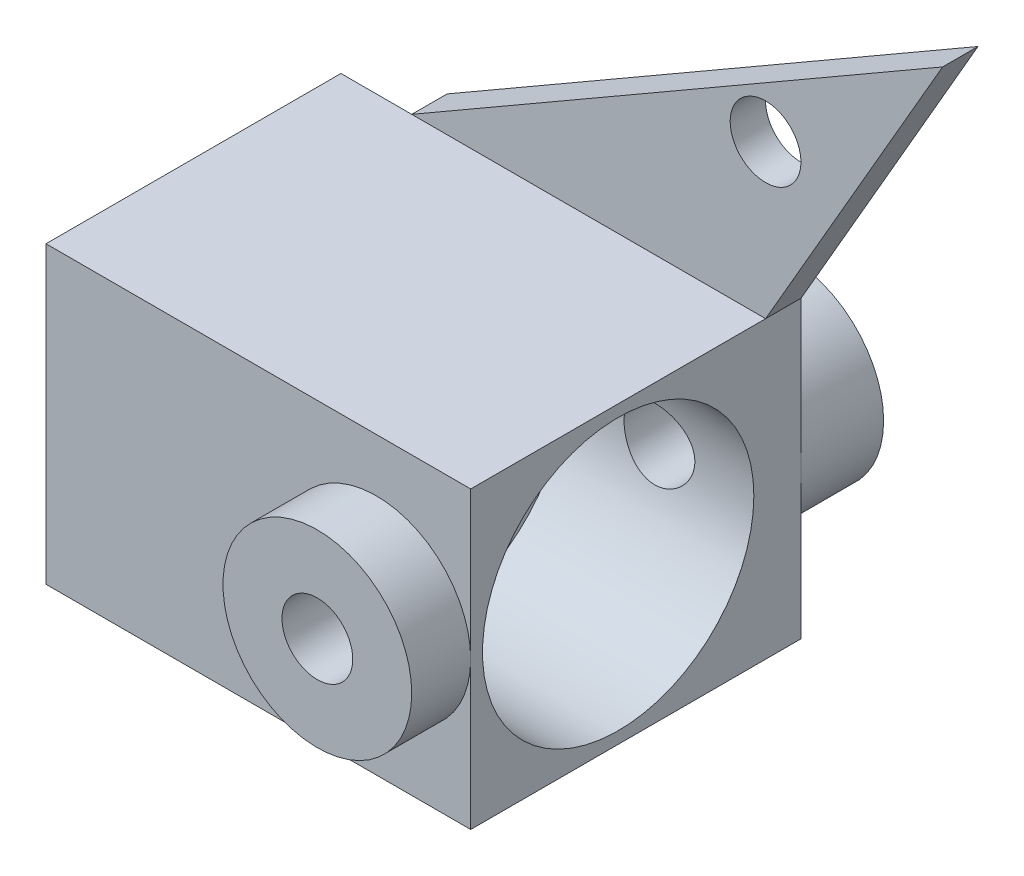
SolidWorks part; units mm, degrees
ref_plane "前视基准面" through (0, 0, 0) normal (0, 0, 1) x (1, 0, 0)
ref_plane "上视基准面" through (0, 0, 0) normal (0, 1, 0) x (1, 0, 0)
ref_plane "右视基准面" through (0, 0, 0) normal (1, 0, 0) x (0, 0, -1)
other "Configuration Table"
sketch "草图1" plane through (0, 0, 0) normal (0, 0, 1) x (1, 0, 0)
  line L0 (-52.6872, 0) -> (52.6872, 0) construction
  line L1 (0, -45.2005) -> (0, 45.2005) construction
  line L3 (-17.5, 12.5) -> (17.5, 12.5)
  line L4 (-17.5, 12.5) -> (-17.5, -12.5)
  line L5 (-17.5, -12.5) -> (17.5, -12.5)
  line L6 (17.5, 12.5) -> (17.5, -12.5)
  circle A0 centre (9.5, 0) radius 8
  point P4 (0, 0)
  point P8 (0, 0)
  dimension "D1" = 35
  dimension "D2" = 25
extrude "凸台-拉伸2" add sketch "草图1" along normal blind 25 contours L6 A0 L3 L4 L5 | A0
sketch "草图2" plane through (0, 0, 25) normal (0, 0, 1) x (1, 0, 0)
  line L0 (0, 0) -> (50000, 0) construction
  line L1 (0, 0) -> (0, 50000) construction
  line L2 (17.5, 12.5) -> (17.5, -12.5) construction
  circle A0 centre (9.5, 0) radius 8
extrude "凸台-拉伸3" add sketch "草图2" along normal blind 5 contours A0
sketch "草图3" plane through (0, 0, 0) normal (0, 0, -1) x (-1, 0, 0)
  line L0 (-17.5, 0) -> (49982.5, 0) construction
  line L1 (0, 0) -> (0, 50000) construction
  line L2 (-17.5, 12.5) -> (-17.5, -12.5) construction
  circle A0 centre (-9.5, 0) radius 8
extrude "凸台-拉伸4" add sketch "草图3" along normal blind 10
sketch "草图4" plane through (0, 0, 30) normal (0, 0, 1) x (1, 0, 0)
  circle A0 centre (9.5, 0) radius 3
extrude "切除-拉伸1" cut sketch "草图4" against normal through all contours A0
sketch "草图5" plane through (17.5, 0, 0) normal (1, 0, 0) x (0, 0, -1)
  line L0 (-12.5, 40.5372) -> (-12.5, -15.5372) construction
  line L2 (-25, 0) -> (49975, 0) construction
  circle A0 centre (-12.5, 0) radius 11.5
  point P3 (-12.5, 12.5)
extrude "切除-拉伸2" cut sketch "草图5" against normal blind 16
sketch "草图6" plane through (-17.5, 0, 0) normal (-1, 0, 0) x (0, 0, 1)
  line L0 (0, 0) -> (50000, 0) construction
  line L1 (12.5, 12.5) -> (12.5, 50012.5) construction
  line L2 (25, 12.5) -> (0, 12.5) construction
  circle A0 centre (12.5, 0) radius 4
  point P7 (12.5, 12.5)
extrude "凸台-拉伸5" add sketch "草图6" along normal blind 15
sketch "草图8" plane through (-17.5, 0, 0) normal (-1, 0, 0) x (0, 0, 1)
  line L0 (0, 0) -> (50000, 0) construction
  line L1 (12.5, 0) -> (12.5, 50000) construction
  line L3 (18.5, -1.0127) -> (15.5, -1.0127)
  line L4 (18.5, -1.0127) -> (18.5, 1.0127)
  line L5 (18.5, 1.0127) -> (15.5, 1.0127)
  line L6 (15.5, -1.0127) -> (15.5, 1.0127)
  dimension "D1" = 3
  dimension "D2" = 3
extrude "切除-拉伸3" cut sketch "草图8" along normal blind 15 contours L4 L3 L6 L5
sketch "草图9" plane through (-32.5, 0, 0) normal (-1, 0, 0) x (0, 0, 1)
  circle A0 centre (12.5, 0) radius 4
extrude "凸台-拉伸6" add sketch "草图9" against normal blind 2
sketch "草图10" plane through (-17.5, 0, 0) normal (-1, 0, 0) x (0, 0, 1)
  circle A0 centre (12.5, 0) radius 4
extrude "凸台-拉伸7" add sketch "草图10" along normal blind 2
sketch "草图12" plane through (0, 0, 0) normal (0, 0, -1) x (-1, 0, 0)
  line L0 (-17.5, -12.5) -> (12.5, -12.5)
  line L1 (17.5, -12.5) -> (-17.5, -12.5) construction
  line L4 (12.5, -12.5) -> (-32.5, -38.4808)
  line L5 (-32.5, -38.4808) -> (-2.5, -12.5)
  line L6 (-17.5, -12.5) -> (-32.5, -38.4808)
  line L7 (-17.5, -12.5) -> (-17.5, -25.4904)
  line L8 (12.5, -12.5) -> (12.5, 12.5)
  line L9 (17.5, 12.5) -> (-17.5, 12.5) construction
  line L10 (12.5, 12.5) -> (-17.5, 12.5)
  line L11 (-17.5, 12.5) -> (-17.5, -12.5)
  line L13 (-17.5, -12.5) -> (-24.1279, -12.5)
  line L14 (-17.5, -12.5) -> (-17.5, 12.5)
  line L15 (-17.5, 12.5) -> (-24.1279, 12.5)
  line L16 (-24.1279, -12.5) -> (-24.1279, 12.5)
  circle A1 centre (-17.5, -25.4904) radius 3
  circle A2 centre (-9.5, 0) radius 8
  line M7 (-17.5, 12.5) -> (-17.5, 0)
  circle M8 centre (-9.5, 0) radius 8
  line M9 (-17.5, 0) -> (-17.5, -12.5)
  line M10 (-17.5, -12.5) -> (17.5, -12.5)
  line M12 (17.5, 12.5) -> (-17.5, 12.5)
  dimension "D1" = 30
  dimension "D2" = 120
extrude "凸台-拉伸11" add sketch "草图12" along normal blind 3 contours L0 L8 M12 M7 M8 M9 M10 | L16 L13 L15 M9 M7 | A1 L5 L7 M10 | A1 L7 L6 L5 | A1 L5 L4 L0
sketch "草图14" plane through (0, 0, 0) normal (0, 0, 1) x (1, 0, 0)
  line L0 (24.1279, -12.5) -> (24.1279, 12.5) construction
  line L1 (17.5, 12.5) -> (24.1279, 12.5)
  line L2 (17.5, 12.5) -> (17.5, -12.5)
  line L3 (17.5, -12.5) -> (24.1279, -12.5)
  line L4 (24.1279, 12.5) -> (24.1279, -12.5)
extrude "切除-拉伸4" cut sketch "草图14" against normal blind 3 contours L2 L1 L4 L3
sketch "草图15" plane through (0, 0, -3) normal (0, 0, -1) x (-1, 0, 0)
  line L0 (-17.5, 12.5) -> (-32.5, 38.4808)
  line L1 (-32.5, 38.4808) -> (12.5, 12.5)
  line L2 (-17.5, 12.5) -> (12.5, 12.5)
  circle A0 centre (-17.4917, 25.4856) radius 3
  dimension "D1" = 6.5
  dimension "D2" = 3.75
extrude "凸台-拉伸12" add sketch "草图15" against normal blind 3
sketch "草图16" plane through (0, 0, 0) normal (0, 0, 1) x (1, 0, 0)
  line L0 (-12.5, -12.5) -> (32.5, -38.4808) construction
  line L1 (-12.5, -12.5) -> (41.6085, -12.5)
  line L2 (-12.5, -12.5) -> (-12.5, -42.6509)
  line L3 (-12.5, -42.6509) -> (41.6085, -42.6509)
  line L4 (41.6085, -12.5) -> (41.6085, -42.6509)
  line L5 (17.5, -12.5) -> (-12.5, -12.5) construction
extrude "切除-拉伸5" cut sketch "草图16" against normal through all
sketch "草图17" plane through (-17.5, 0, 0) normal (-1, 0, 0) x (0, 0, 1)
  line L0 (25, 12.5) -> (25, -12.5) construction
  line L1 (0, 12.5) -> (25, 12.5)
  line L2 (0, 12.5) -> (0, -12.5)
  line L3 (0, -12.5) -> (25, -12.5)
  line L4 (25, 12.5) -> (25, -12.5)
  line L5 (25, -12.5) -> (0, -12.5) construction
extrude "切除-拉伸6" cut sketch "草图17" along normal through all
sketch "草图18" plane through (-17.5, 0, 0) normal (-1, 0, 0) x (0, 0, 1)
  line L0 (-37.3003, 0) -> (37.3003, 0) construction
  line L2 (12.5, 12.5) -> (12.5, 50012.5) construction
  line L3 (25, 12.5) -> (0, 12.5) construction
  line L5 (0, 12.5) -> (25, 12.5)
  line L6 (0, 12.5) -> (0, -12.5)
  line L7 (0, -12.5) -> (25, -12.5)
  line L8 (25, 12.5) -> (25, -12.5)
  circle A0 centre (12.5, 0) radius 4
  point P4 (0, 0)
  point P9 (12.5, 12.5)
extrude "凸台-拉伸13" add sketch "草图18" along normal blind 1
